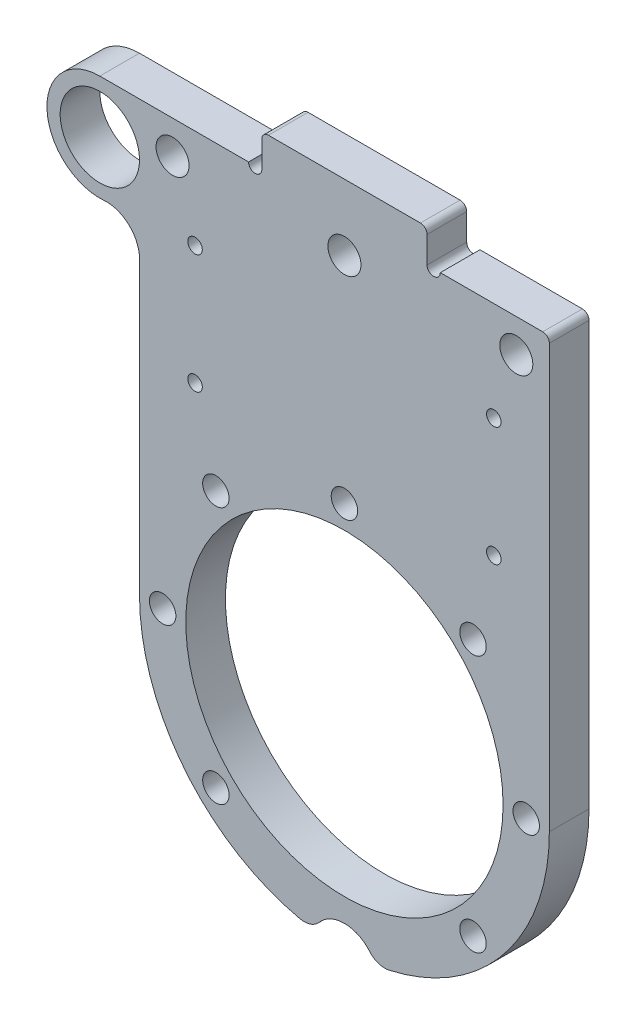
SolidWorks part; units mm, degrees
material "Thornel Mat VMA"
ref_plane "前视基准面" through (0, 0, 0) normal (0, 0, 1) x (1, 0, 0)
ref_plane "上视基准面" through (0, 0, 0) normal (0, 1, 0) x (1, 0, 0)
ref_plane "右视基准面" through (0, 0, 0) normal (1, 0, 0) x (0, 0, -1)
sketch "草图1" plane through (0, 0, 0) normal (0, 0, 1) x (1, 0, 0)
  line L0 (-31, 0) -> (-31, 44.0385)
  line L1 (-37, 65) -> (-12.5, 65)
  line L2 (31, 65) -> (31, 0)
  line L3 (0, 70) -> (0, -32.5) construction
  line L8 (12.5, 65) -> (31, 65)
  line L10 (-12.5, 65) -> (-12.5, 70)
  line L11 (-12.5, 70) -> (12.5, 70)
  line L12 (12.5, 65) -> (12.5, 70)
  line L13 (-26, 60) -> (26, 60) construction
  line L15 (-22.6, 50) -> (22.6, 50) construction
  line L16 (-22.6, 50) -> (-22.6, 32) construction
  line L17 (-22.6, 32) -> (22.6, 32) construction
  line L18 (22.6, 50) -> (22.6, 32) construction
  circle A0 centre (0, 0) radius 24
  arc A1 (-31, 0) -> (-6.7562, -30.2548) centre (0, 0) ccw
  circle A2 centre (0, 0) radius 27.5 construction
  circle A3 centre (-19.4454, 19.4454) radius 2
  circle A4 centre (0, 27.5) radius 2
  circle A5 centre (19.4454, 19.4454) radius 2
  circle A6 centre (27.5, 0) radius 2
  arc A7 (3.814, -29.2668) -> (-3.814, -29.2668) centre (0, -32.5) ccw
  arc A8 (6.7562, -30.2548) -> (31, 0) centre (0, 0) ccw
  arc A9 (3.814, -29.2668) -> (6.7562, -30.2548) centre (6.1024, -27.3269) ccw
  arc A10 (-3.814, -29.2668) -> (-6.7562, -30.2548) centre (-6.1024, -27.3269) cw
  circle A11 centre (19.4454, -19.4454) radius 2
  circle A12 centre (0, -27.5) radius 2 construction
  circle A13 centre (-19.4454, -19.4454) radius 2
  circle A14 centre (-27.5, 0) radius 2
  circle A15 centre (-26, 60) radius 2.5
  circle A16 centre (0, 60) radius 2.5
  circle A17 centre (26, 60) radius 2.5
  circle A18 centre (-22.6, 50) radius 1.1
  circle A19 centre (-22.6, 32) radius 1.1
  circle A20 centre (22.6, 32) radius 1.1
  circle A21 centre (22.6, 50) radius 1.1
  arc A22 (-37, 65) -> (-36.3846, 49.0237) centre (-37, 57) ccw
  circle A23 centre (-37, 57) radius 6
  arc A24 (-31, 44.0385) -> (-36.3846, 49.0237) centre (-36, 44.0385) ccw
  point P45 (0, 32)
  point P51 (-38.7895, 55.1248)
  point P52 (-31, 56.3615)
  point P54 (-31, 56.3412)
  point P57 (0, 70)
  point P58 (0, 60)
  point P59 (-31, 45.5363)
  point P60 (-36.5551, 58)
  point P61 (0, 0)
  dimension "D1" = 48
  dimension "D2" = 31
  dimension "D3" = 3.5
  dimension "D4" = 4
  dimension "D8" = 5
  dimension "D10" = 3
  dimension "D11" = 25
  dimension "D12" = 5
  dimension "D13" = 5
  dimension "D14" = 5
  dimension "D15" = 45.2
  dimension "D18" = 2.2
  dimension "D19" = 12
  dimension "D20" = 2
  dimension "D21" = 5
  dimension "D6" = 52
  dimension "D7" = 65
  dimension "D9" = 32.5
  dimension "D16" = 18
  dimension "D17" = 10
  dimension "D5" = 8
extrude "凸台-拉伸1" add sketch "草图1" along normal blind 6
sketch "草图2" plane through (0, 0, 6) normal (0, 0, 1) x (1, 0, 0)
  line L0 (-12.5, 65) -> (-37, 65) construction
  line L1 (31, 65) -> (12.5, 65) construction
  circle A0 centre (-13.5, 65) radius 1
  circle A1 centre (13.5, 65) radius 1
  dimension "D1" = 2
extrude "切除-拉伸1" cut sketch "草图2" against normal through all
fillet "圆角1" radius 1 3 edges at (31, 65, 3) (12.5, 70, 3) (-12.5, 70, 3)
